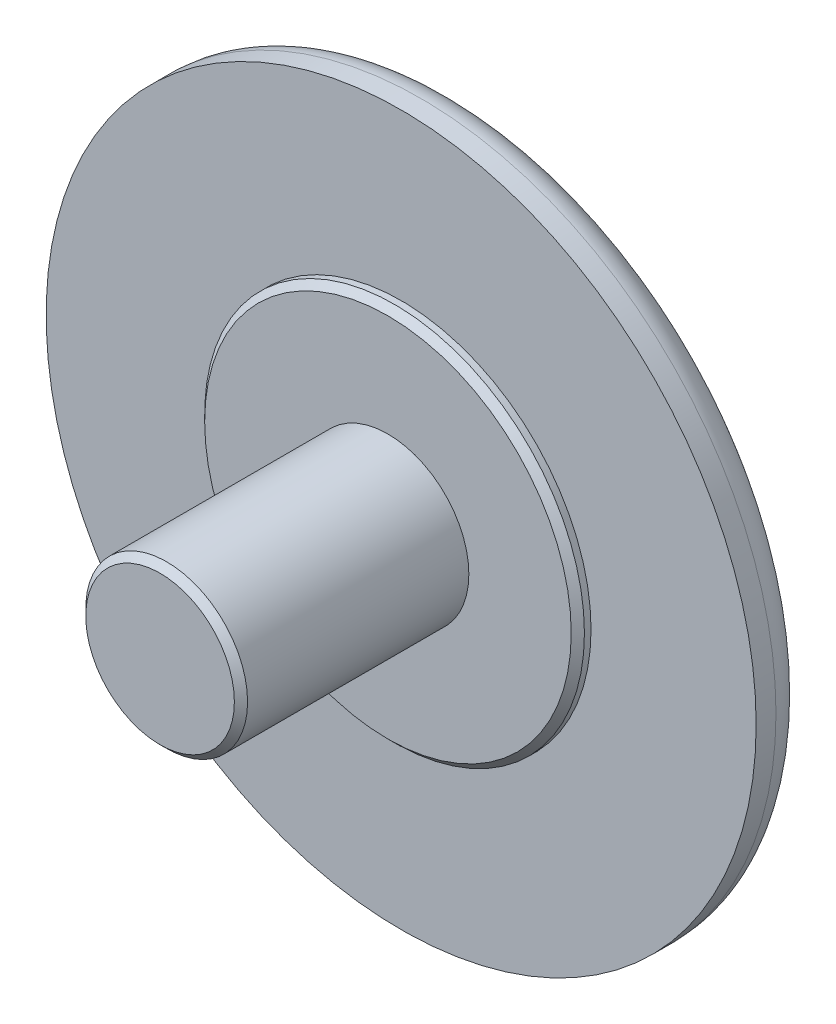
SolidWorks part; units mm, degrees
ref_plane "Front Plane" through (0, 0, 0) normal (0, 0, 1) x (1, 0, 0)
ref_plane "Top Plane" through (0, 0, 0) normal (0, 1, 0) x (1, 0, 0)
ref_plane "Right Plane" through (0, 0, 0) normal (1, 0, 0) x (0, 0, -1)
sketch "Sketch1" plane through (0, 0, 0) normal (0, 1, 0) x (1, 0, 0)
  line L0 (2.45, 0) -> (0, 0)
  line L1 (0, 0) -> (0, 8.9)
  line L2 (0, 8.9) -> (9.75, 8.9)
  line L3 (10.75, 7.9) -> (10.75, 7.3)
  line L4 (10.75, 7.3) -> (5.75, 7.3)
  line L5 (5.75, 7.3) -> (5.75, 6.9)
  line L6 (5.75, 6.9) -> (2.45, 6.9)
  line L7 (2.45, 6.9) -> (2.45, 0)
  arc A0 (9.75, 8.9) -> (10.75, 7.9) centre (9.75, 7.9) cw
  point P11 (10.75, 8.9)
  dimension "D8" = 1
  dimension "D1" = 8.9
  dimension "D2" = 6.9
  dimension "D3" = 0.4
  dimension "D4" = 2
  dimension "D5" = 2.45
  dimension "D6" = 5.75
  dimension "D7" = 10.75
revolve "Revolve1" add sketch "Sketch1" angle 360 about L1
chamfer "Chamfer1" distance 0.2 angle 45 1 edges at (5.75, 0, -6.9)
chamfer "Chamfer2" distance 0.2 angle 45 1 edges at (2.45, 0, 0)
